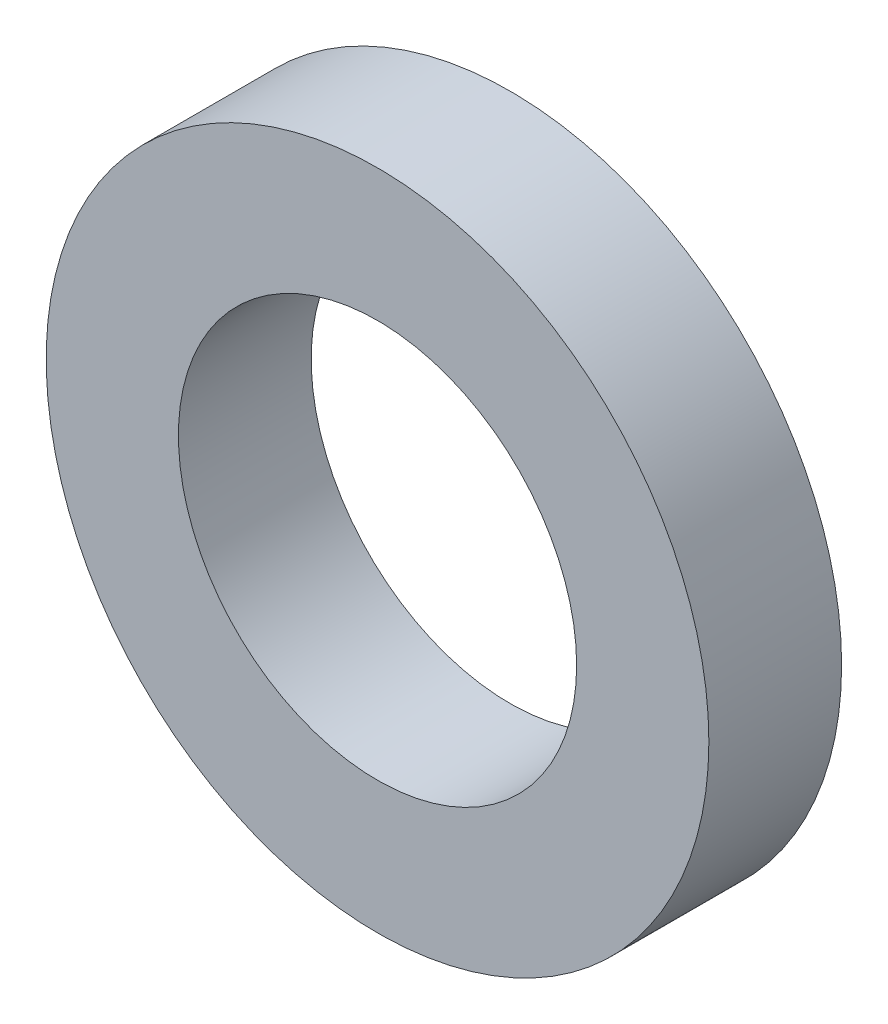
SolidWorks part; units mm, degrees
ref_plane "Front Plane" through (0, 0, 0) normal (0, 0, 1) x (1, 0, 0)
ref_plane "Top Plane" through (0, 0, 0) normal (0, 1, 0) x (1, 0, 0)
ref_plane "Right Plane" through (0, 0, 0) normal (1, 0, 0) x (0, 0, -1)
sketch "Sketch1" plane through (0, 0, 0) normal (0, 0, 1) x (1, 0, 0)
  circle A0 centre (0, 0) radius 2.3813
  circle A1 centre (0, 0) radius 3.9624
  dimension "D1" = 4.7625
  dimension "D2" = 7.9248
extrude "Boss-Extrude1" add sketch "Sketch1" along normal blind 1.5875
